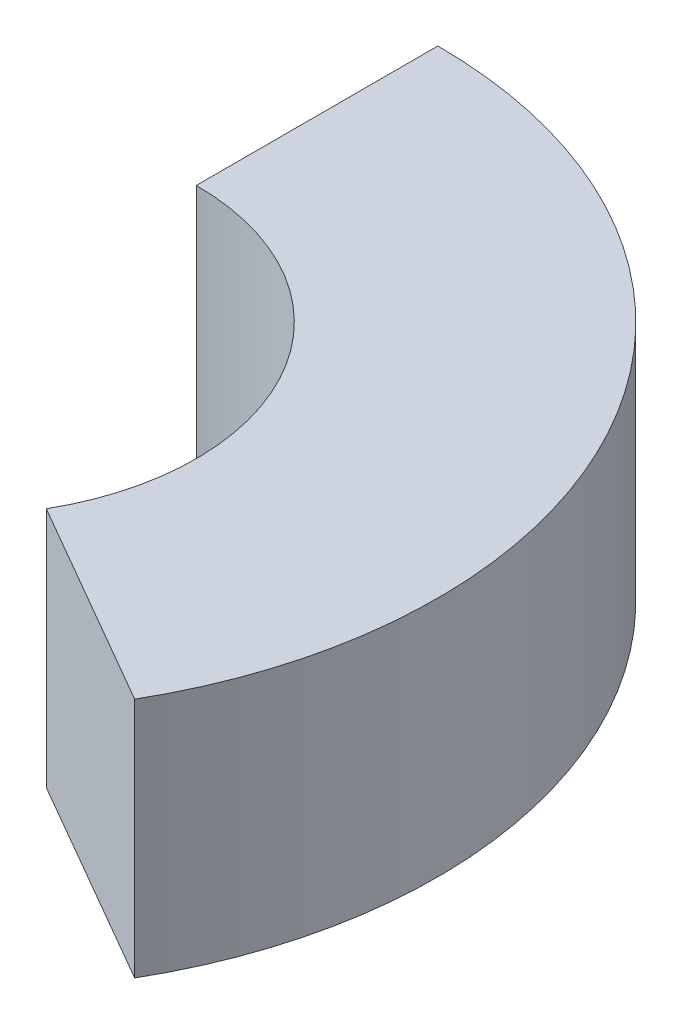
SolidWorks part; units mm, degrees
ref_plane "Front Plane" through (0, 0, 0) normal (0, 0, 1) x (1, 0, 0)
ref_plane "Top Plane" through (0, 0, 0) normal (0, 1, 0) x (1, 0, 0)
ref_plane "Right Plane" through (0, 0, 0) normal (1, 0, 0) x (0, 0, -1)
sketch "Sketch1" plane through (0, 0, 0) normal (0, 1, 0) x (1, 0, 0)
  line L0 (0, 147) -> (0, 297)
  line L1 (127.3057, -73.5) -> (257.2095, -148.5)
  arc A0 (0, 147) -> (127.3057, -73.5) centre (0, 0) cw
  arc A1 (0, 297) -> (257.2095, -148.5) centre (0, 0) cw
  circle A2 centre (0, 0) radius 147
  dimension "D1" = 120
  dimension "D3" = 150
  dimension "D4" = 294
  dimension "D2" = 150
extrude "Boss-Extrude1" add sketch "Sketch1" along normal blind 150 contours A1 L0 A0 L1
